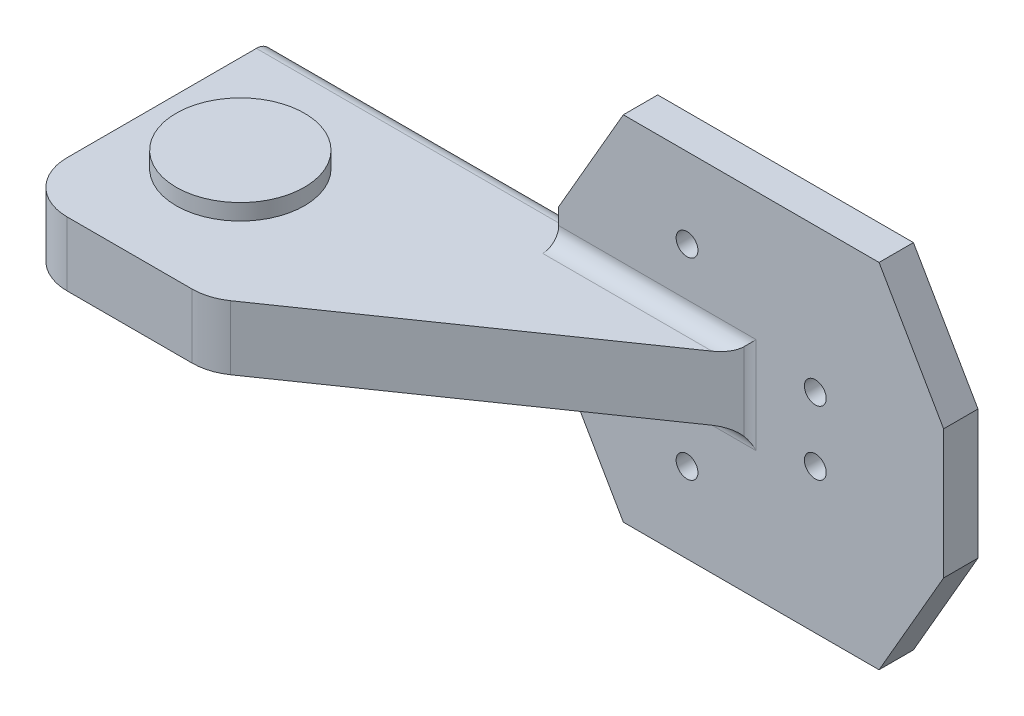
SolidWorks part; units mm, degrees
material "PET"
ref_plane "Front Plane" through (0, 0, 0) normal (0, 0, 1) x (1, 0, 0)
ref_plane "Top Plane" through (0, 0, 0) normal (0, 1, 0) x (1, 0, 0)
ref_plane "Right Plane" through (0, 0, 0) normal (1, 0, 0) x (0, 0, -1)
sketch "Sketch1" plane through (0, 0, 0) normal (0, 1, 0) x (1, 0, 0)
  line L0 (0, 0) -> (38.1, 0) construction
  line L1 (0, 25.4) -> (38.1, 25.4)
  line L2 (0, -25.4) -> (38.1, -25.4)
  line L3 (38.1, 25.4) -> (101.6, 25.4)
  line L4 (101.6, 25.4) -> (101.6, 18.5941)
  line L5 (101.6, 18.5941) -> (38.1, -25.4)
  line L6 (0, 25.4) -> (0, -25.4)
  point P3 (25.4, 0)
  dimension "D1" = 101.6
  dimension "D2" = 38.1
  dimension "D3" = 50.8
extrude "Boss-Extrude1" add sketch "Sketch1" along normal blind 12.7
sketch "Sketch2" plane through (0, 0, -25.4) normal (0, 0, -1) x (-1, 0, 0)
  line L0 (-63.5, 19.1334) -> (-63.5, -6.4334)
  line L3 (-63.5, -6.4334) -> (-76.2834, -28.575)
  line L4 (-76.2834, -28.575) -> (-126.9166, -28.575)
  line L5 (-126.9166, -28.575) -> (-139.7, -6.4334)
  line L6 (-139.7, -6.4334) -> (-139.7, 19.1334)
  line L7 (-63.5, 6.35) -> (-192.9249, 6.35) construction
  line L8 (-101.6, 12.7) -> (-101.6, 0) construction
  line L9 (-63.5, 19.1334) -> (-76.2834, 41.275)
  line L10 (-76.2834, 41.275) -> (-126.9166, 41.275)
  line L11 (-126.9166, 41.275) -> (-139.7, 19.1334)
  point P5 (-101.6, 6.35)
  point P13 (-139.7, 6.35)
  dimension "D1" = 34.925
  dimension "D2" = 76.2
  dimension "D3" = 38.1
  dimension "D4" = 120
extrude "Boss-Extrude2" add sketch "Sketch2" against normal up to vertex (6.8059 mm away) contours L5 L6 L11 L10 L9 L0 L3 L4
sketch "Sketch3" plane through (0, 0, -25.4) normal (0, 0, -1) x (-1, 0, 0)
  line L0 (-139.7, 6.35) -> (-48.482, 6.35) construction
  line L1 (-139.7, -6.4334) -> (-139.7, 19.1334) construction
  line L2 (-63.5, 19.1334) -> (-63.5, 12.7) construction
  circle A0 centre (-88.9, 25.4) radius 2.159
  circle A1 centre (-88.9, 25.4) radius 19.05 construction
  circle A2 centre (-88.9, -12.7) radius 2.159
  circle A3 centre (-88.9, -12.7) radius 19.05 construction
  circle A9 centre (-88.9, 25.4) radius 22.225
  point P20 (-114.3, 6.35)
  dimension "D1" = 4.318
  dimension "D3" = 38.1
  dimension "D4" = 3.175
  dimension "D2" = 25.4
extrude "Cut-Extrude1" cut sketch "Sketch3" against normal through all contours A0 | A2
sketch "Sketch5" plane through (0, 0, -25.4) normal (0, 0, -1) x (-1, 0, 0)
  line L1 (-139.7, 6.35) -> (-151.0753, 6.35) construction
  line L2 (-139.7, -6.4334) -> (-139.7, 19.1334) construction
  circle A0 centre (-114.3, 12.7) radius 2.159
  circle A1 centre (-114.3, 0) radius 2.159
  circle A2 centre (-88.9, 25.4) radius 2.159 construction
  dimension "D2" = 4.318
  dimension "D1" = 25.4
  dimension "D3" = 12.7
extrude "Cut-Extrude2" cut sketch "Sketch5" against normal up to surface (6.8059 mm away) contours A1 | A0 up to face at (91.059, -12.7, -18.5941)
fillet "Fillet1" radius 3.175 5 edges at (82.55, 0, -18.5941) (101.6, 6.35, -18.5941) (82.55, 12.7, -18.5941) (31.75, 0, -25.4) (31.75, 12.7, -25.4)
sketch "Sketch6" plane through (0, 12.7, 0) normal (0, 1, 0) x (1, 0, 0)
  line L0 (0, 22.225) -> (0, -25.4) construction
  circle A0 centre (19.05, 0) radius 12.7
  dimension "D1" = 19.05
  dimension "D2" = 25.4
extrude "Boss-Extrude3" add sketch "Sketch6" along normal blind 3.175
fillet "Fillet2" radius 10.16 2 edges at (0, 6.35, 25.4) (38.1, 6.35, 25.4)
